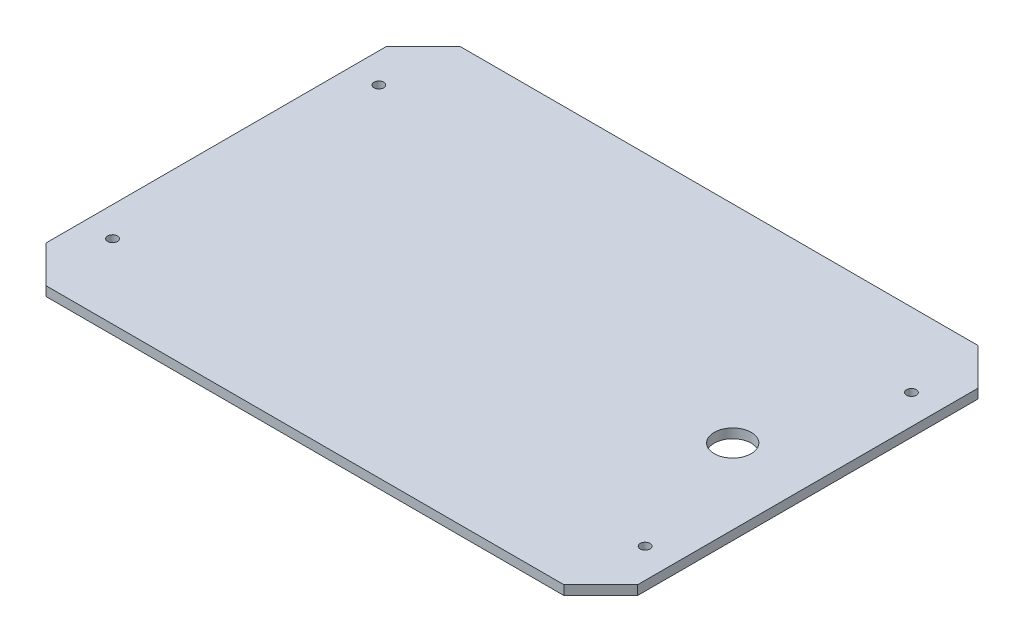
SolidWorks part; units mm, degrees
ref_plane "Front Plane" through (0, 0, 0) normal (0, 0, 1) x (1, 0, 0)
ref_plane "Top Plane" through (0, 0, 0) normal (0, 1, 0) x (1, 0, 0)
ref_plane "Right Plane" through (0, 0, 0) normal (1, 0, 0) x (0, 0, -1)
sketch "Sketch1" plane through (0, 0, 0) normal (0, 1, 0) x (1, 0, 0)
  line L1 (0, 0) -> (400, 0)
  line L2 (0, 0) -> (0, 280)
  line L3 (0, 280) -> (400, 280)
  line L4 (400, 0) -> (400, 280)
  dimension "D1" = 400
  dimension "D2" = 280
extrude "Boss-Extrude1" add sketch "Sketch1" along normal blind 6.35
chamfer "Chamfer1" distance 25 angle 45 4 edges at (0, 3.175, 0) (0, 3.175, -280) (400, 3.175, -280) (400, 3.175, 0)
sketch "Sketch2" plane through (0, 6.35, 0) normal (0, 1, 0) x (1, 0, 0)
  line L0 (400, 25) -> (400, 255) construction
  line L1 (400, 140) -> (0, 140) construction
  line L2 (0, 255) -> (0, 25) construction
  circle A0 centre (349.2, 140) radius 12.5
  point P8 (0, 0)
  dimension "D1" = 25
  dimension "D2" = 50.8
extrude "Cut-Extrude1" cut sketch "Sketch2" against normal through all
hole_wizard "M6 Clearance Hole1" positions "Sketch3" profile "Sketch4" hole size "M6" standard "ANSI Metric" end condition through all
sketch "Sketch3" plane through (0, 6.35, 0) normal (0, 1, 0) x (1, 0, 0)
  line L0 (375, 280) -> (25, 280) construction
  line L1 (400, 25) -> (400, 255) construction
  line L2 (400, 140) -> (0, 140) construction
  line L3 (0, 255) -> (0, 25) construction
  line L6 (200, 280) -> (200, 0) construction
  line L7 (25, 0) -> (375, 0) construction
  point P0 (380, 230)
  point P21 (380, 50)
  point P22 (20, 50)
  point P23 (20, 230)
  dimension "D1" = 50
  dimension "D2" = 20
sketch "Sketch4" plane through (380, 6.35, -230) normal (1, 0, 0) x (0, 0, 1)
  line L0 (0, 0) -> (0, 6.35)
  line L1 (0, 6.35) -> (3.3, 6.35)
  line L2 (3.3, 6.35) -> (3.3, 0)
  line L5 (3.3, 0) -> (0, 0)
  line L11 (0, -6.35) -> (0, 107.95) construction
  dimension "Thru Hole Dia." = 6.6
  dimension "Thru Hole Depth" = 6.35
